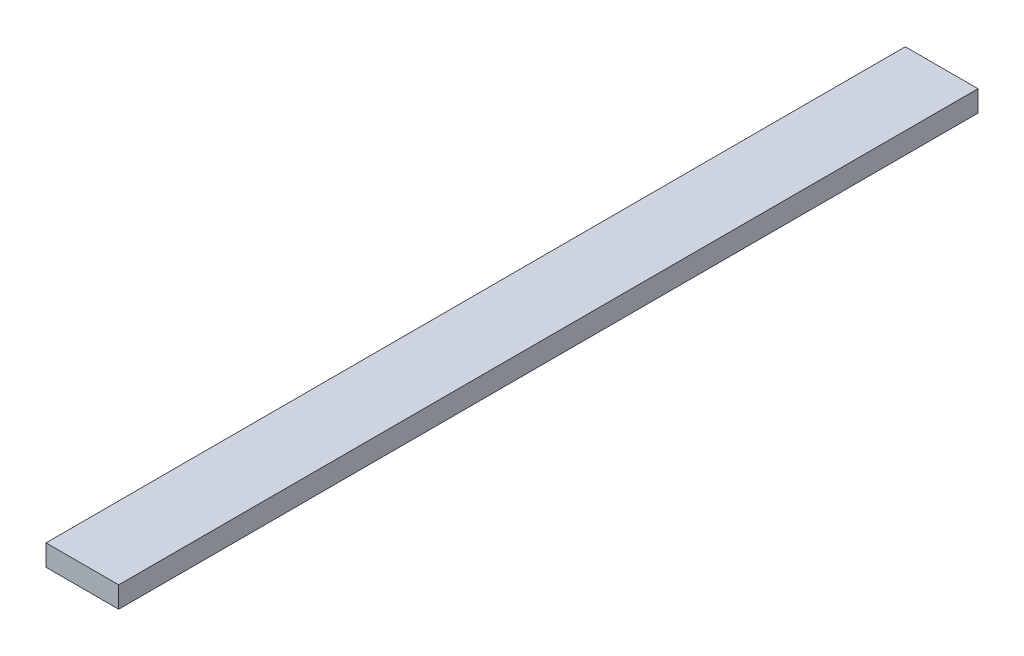
SolidWorks part; units mm, degrees
ref_plane "Front Plane" through (0, 0, 0) normal (0, 0, 1) x (1, 0, 0)
ref_plane "Top Plane" through (0, 0, 0) normal (0, 1, 0) x (1, 0, 0)
ref_plane "Right Plane" through (0, 0, 0) normal (1, 0, 0) x (0, 0, -1)
sketch "Sketch1" plane through (0, 0, 0) normal (0, 1, 0) x (1, 0, 0)
  line L1 (-6.1442, 145.3092) -> (7.8258, 145.3092)
  line L2 (-6.1442, 145.3092) -> (-6.1442, -19.7908)
  line L3 (-6.1442, -19.7908) -> (7.8258, -19.7908)
  line L4 (7.8258, 145.3092) -> (7.8258, -19.7908)
  dimension "D1" = 13.97
  dimension "D2" = 165.1
extrude "Boss-Extrude1" add sketch "Sketch1" along normal blind 2.54
sketch "Sketch2" plane through (0, 2.54, 0) normal (0, 1, 0) x (1, 0, 0)
  line L1 (-6.1442, -19.7908) -> (7.8258, -19.7908)
  line L2 (-6.1442, -19.7908) -> (-6.1442, 145.3092)
  line L3 (-6.1442, 145.3092) -> (7.8258, 145.3092)
  line L4 (7.8258, -19.7908) -> (7.8258, 145.3092)
extrude "Boss-Extrude2" add sketch "Sketch2" along normal blind 1.524
